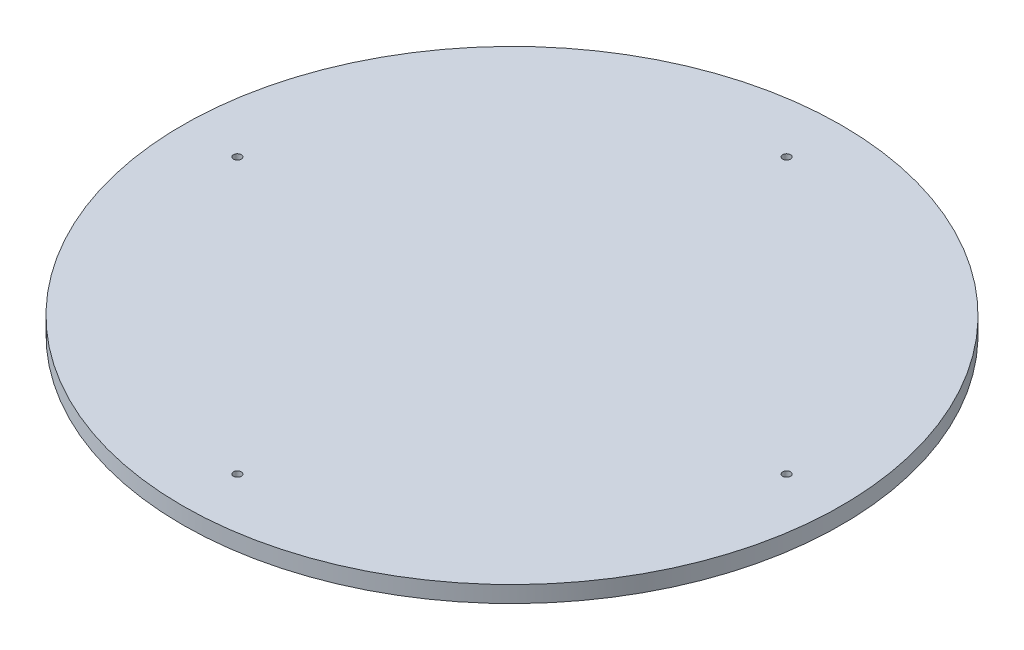
SolidWorks part; units mm, degrees
ref_plane "Front Plane" through (0, 0, 0) normal (0, 0, 1) x (1, 0, 0)
ref_plane "Top Plane" through (0, 0, 0) normal (0, 1, 0) x (1, 0, 0)
ref_plane "Right Plane" through (0, 0, 0) normal (1, 0, 0) x (0, 0, -1)
sketch "Sketch1" plane through (0, 0, 0) normal (0, 1, 0) x (1, 0, 0)
  circle A0 centre (0, 0) radius 300
  dimension "D1" = 600
extrude "Boss-Extrude1" add sketch "Sketch1" along normal blind 15
sketch "Extrusion Hole locations" plane through (0, 0, 0) normal (0, 1, 0) x (1, 0, 0)
  point P3 (0, 250)
  point P14 (250, 0)
  point P15 (0, -250)
  point P16 (-250, 0)
  dimension "D2" = 250
  dimension "D4" = 4
hole_wizard "CBORE for 1/4 Socket Head Cap Screw1" positions "Extrusion Hole locations" profile "Sketch3" counterbore size "1/4" standard "ANSI Inch" end condition through all
sketch "Sketch3" plane through (-250, 0, 0) normal (1, 0, 0) x (0, 0, -1)
  line L0 (0, 0) -> (0, 15)
  line L1 (0, 15) -> (3.5712, 15)
  line L3 (3.5712, 15) -> (3.5712, 6.35)
  line L4 (3.5712, 6.35) -> (5.5562, 6.35)
  line L5 (5.5562, 6.35) -> (5.5562, 0)
  line L7 (5.5562, 0) -> (0, 0)
  line L11 (0, -6.35) -> (0, 107.95) construction
  dimension "Thru Hole Dia." = 7.1425
  dimension "Thru Hole Depth" = 15
  dimension "C'Bore Dia." = 11.1125
  dimension "C'Bore Depth" = 6.35
